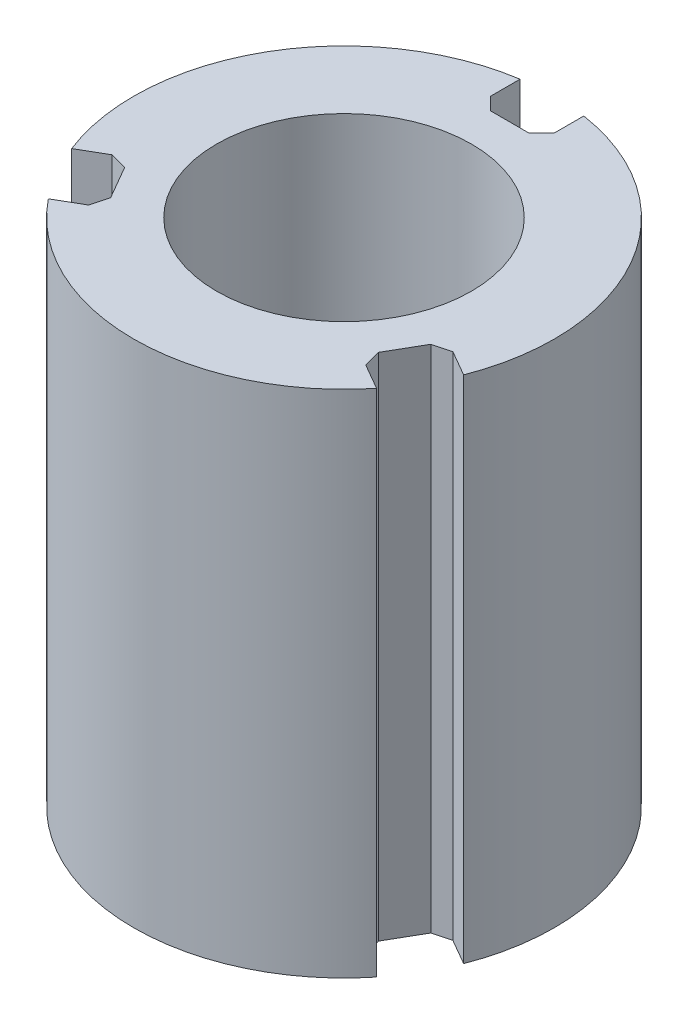
SolidWorks part; units mm, degrees
ref_plane "Front Plane" through (0, 0, 0) normal (0, 0, 1) x (1, 0, 0)
ref_plane "Top Plane" through (0, 0, 0) normal (0, 1, 0) x (1, 0, 0)
ref_plane "Right Plane" through (0, 0, 0) normal (1, 0, 0) x (0, 0, -1)
sketch "Sketch1" plane through (0, 0, 0) normal (0, 1, 0) x (1, 0, 0)
  line L0 (0, 3.3) -> (0, -3.3) construction
  line L1 (3.3, 0) -> (-3.3, 0) construction
  line L2 (-0.5, 2.8) -> (-0.3, 2.6)
  line L4 (-0.5, 3.2619) -> (-0.5, 2.8)
  line L5 (-0.3, 2.6) -> (0.3, 2.6)
  line L6 (0.5, 3.2619) -> (0.5, 2.8)
  line L7 (0, 3.3) -> (0.5, 2.6) construction
  line L8 (-0.5, 2.6) -> (0, 3.3) construction
  line L9 (0.3, 2.6) -> (0.5, 2.8)
  line L10 (3.0749, -1.1979) -> (2.6749, -0.967)
  line L11 (2.6749, -0.967) -> (2.4017, -1.0402)
  line L12 (2.4017, -1.0402) -> (2.1017, -1.5598)
  line L13 (2.5749, -2.064) -> (2.1749, -1.833)
  line L14 (2.1017, -1.5598) -> (2.1749, -1.833)
  line L15 (-2.5749, -2.064) -> (-2.1749, -1.833)
  line L16 (-2.1749, -1.833) -> (-2.1017, -1.5598)
  line L17 (-2.1017, -1.5598) -> (-2.4017, -1.0402)
  line L18 (-3.0749, -1.1979) -> (-2.6749, -0.967)
  line L19 (-2.4017, -1.0402) -> (-2.6749, -0.967)
  arc A0 (-0.5, 3.2619) -> (-3.0749, -1.1979) centre (0, 0) ccw
  arc A1 (3.0749, -1.1979) -> (0.5, 3.2619) centre (0, 0) ccw
  arc A2 (-2.5749, -2.064) -> (2.5749, -2.064) centre (0, 0) ccw
  circle A3 centre (0, 0) radius 2
  point P30 (0, 0)
  dimension "D1" = 6.6
  dimension "D7" = 4
  dimension "D2" = 2.6
  dimension "D3" = 1
  dimension "D6" = 3
extrude "Boss-Extrude1" add sketch "Sketch1" along normal blind 8
